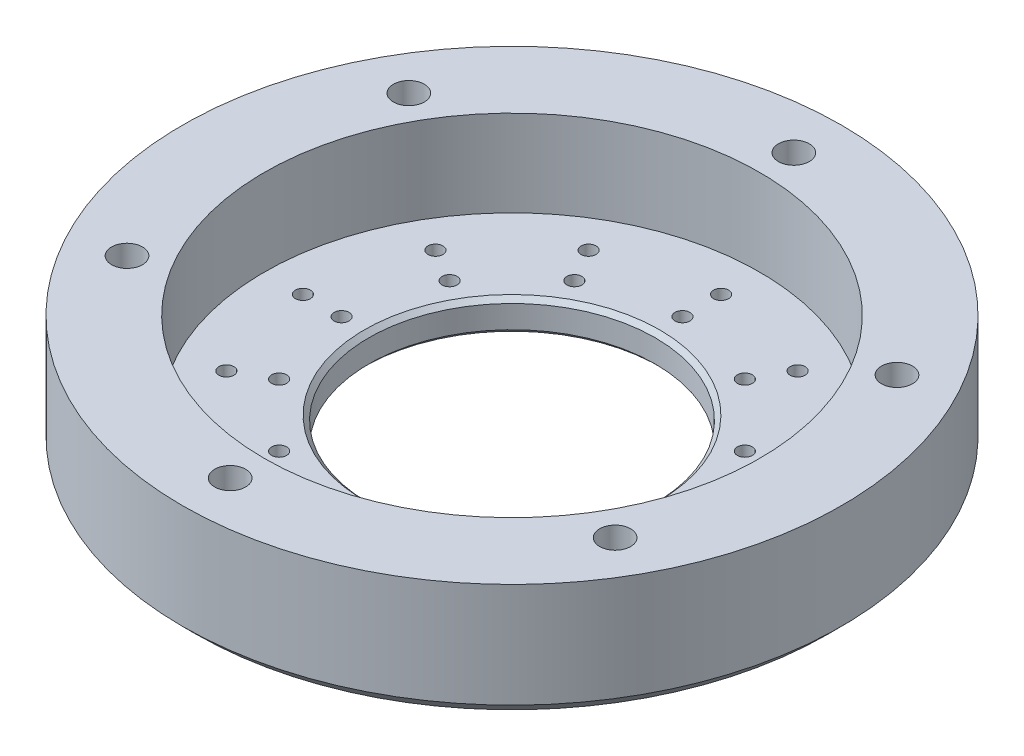
SolidWorks part; units mm, degrees
ref_plane "Piano frontale" through (0, 0, 0) normal (0, 0, 1) x (1, 0, 0)
ref_plane "Piano superiore" through (0, 0, 0) normal (0, 1, 0) x (1, 0, 0)
ref_plane "Piano destro" through (0, 0, 0) normal (1, 0, 0) x (0, 0, -1)
sketch "Schizzo1" plane through (0, 0, 0) normal (0, 0, 1) x (1, 0, 0)
  line L0 (0, 82.5741) -> (0, -57.0556) construction
  line L1 (72.5, 31.5594) -> (72.5, 5.5594)
  line L2 (72.5, 5.5594) -> (31.5, 5.5594)
  line L3 (31.5, 5.5594) -> (31.5, 12.5594)
  line L4 (31.5, 12.5594) -> (54.5, 12.5594)
  line L5 (54.5, 12.5594) -> (54.5, 31.5594)
  line L6 (54.5, 31.5594) -> (72.5, 31.5594)
  point P7 (58.1763, 32.9815)
  point P10 (72.5, 5.5594)
  dimension "D1" = 26
  dimension "D2" = 145
  dimension "D3" = 63
  dimension "D4" = 19
  dimension "D5" = 109
revolve "Rivoluzione1" add sketch "Schizzo1" angle 360 about L0
chamfer "Smusso1" distance 3 angle 45 1 edges at (0, 5.5594, 72.5)
chamfer "Smusso2" distance 1 angle 45 2 edges at (0, 5.5594, 31.5) (0, 12.5594, 31.5)
hole_wizard "Foro filettato M8-1" positions "Schizzo2" profile "Schizzo3" tap size "M8" standard "ISO"
sketch "Schizzo2" plane through (0, 31.5594, 0) normal (0, 1, 0) x (1, 0, 0)
  line L0 (0, 0) -> (0, 82.26) construction
  circle A0 centre (0, 0) radius 62 construction
  point P11 (0, 62)
  dimension "D1" = 124
sketch "Schizzo3" plane through (0, 31.5594, -62) normal (1, 0, 0) x (0, 0, 1)
  line L0 (0, 0) -> (0, 21.0429)
  line L1 (0, 21.0429) -> (3.4, 19)
  line L2 (3.4, 19) -> (3.4, 0)
  line L5 (3.4, 0) -> (0, 0)
  line L10 (0, 21.0429) -> (-3.4, 19) construction
  line L11 (0, -6.35) -> (0, 107.95) construction
  dimension "Tap Drill Dia." = 6.8
  dimension "Tap Drill Depth" = 19
  dimension "Drill Angle" = 118
cosmetic thread "Filettatura del foro1" parameters "D1"=16, "D2"=8
pattern_circular "RipetizioneCircolare1" count 6 over 360 about axis through (0, 0, 0) along (0, 1, 0) of "Foro filettato M8-1"
cosmetic thread "Filettatura del foro2" parameters "D1"=16, "D2"=8
cosmetic thread "Filettatura del foro3" parameters "D1"=16, "D2"=8
cosmetic thread "Filettatura del foro4" parameters "D1"=16, "D2"=8
cosmetic thread "Filettatura del foro5" parameters "D1"=16, "D2"=8
cosmetic thread "Filettatura del foro6" parameters "D1"=16, "D2"=8
hole_wizard "Foro filettato M4-1" positions "Schizzo4" profile "Schizzo5" tap size "M4" standard "ISO" end condition through all
sketch "Schizzo4" plane through (0, 12.5594, 0) normal (0, 1, 0) x (1, 0, 0)
  line L0 (0, 0) -> (0, 90.7044) construction
  circle A0 centre (0, 0) radius 46 construction
  circle A1 centre (0, 0) radius 37.5 construction
  point P13 (0, 37.5)
  point P15 (0, 46)
  dimension "D1" = 92
  dimension "D2" = 75
sketch "Schizzo5" plane through (0, 12.5594, -46) normal (1, 0, 0) x (0, 0, 1)
  line L0 (0, 0) -> (0, 7)
  line L1 (0, 7) -> (1.65, 7)
  line L2 (1.65, 7) -> (1.65, 0)
  line L5 (1.65, 0) -> (0, 0)
  line L11 (0, -6.35) -> (0, 107.95) construction
  dimension "Thru Tap Drill Dia." = 3.3
  dimension "Thru Tap Drill Depth" = 7
cosmetic thread "Filettatura del foro7" parameters "D2"=4
cosmetic thread "Filettatura del foro8" parameters "D2"=4
pattern_circular "RipetizioneCircolare2" count 12 over 360 about axis through (0, 0, 0) along (0, 1, 0) of "Foro filettato M4-1"
cosmetic thread "Filettatura del foro9" parameters "D2"=4
cosmetic thread "Filettatura del foro10" parameters "D2"=4
cosmetic thread "Filettatura del foro11" parameters "D2"=4
cosmetic thread "Filettatura del foro12" parameters "D2"=4
cosmetic thread "Filettatura del foro13" parameters "D2"=4
cosmetic thread "Filettatura del foro14" parameters "D2"=4
cosmetic thread "Filettatura del foro15" parameters "D2"=4
cosmetic thread "Filettatura del foro16" parameters "D2"=4
cosmetic thread "Filettatura del foro17" parameters "D2"=4
cosmetic thread "Filettatura del foro18" parameters "D2"=4
cosmetic thread "Filettatura del foro19" parameters "D2"=4
cosmetic thread "Filettatura del foro20" parameters "D2"=4
cosmetic thread "Filettatura del foro21" parameters "D2"=4
cosmetic thread "Filettatura del foro22" parameters "D2"=4
cosmetic thread "Filettatura del foro23" parameters "D2"=4
cosmetic thread "Filettatura del foro24" parameters "D2"=4
cosmetic thread "Filettatura del foro25" parameters "D2"=4
cosmetic thread "Filettatura del foro26" parameters "D2"=4
cosmetic thread "Filettatura del foro27" parameters "D2"=4
cosmetic thread "Filettatura del foro28" parameters "D2"=4
cosmetic thread "Filettatura del foro29" parameters "D2"=4
cosmetic thread "Filettatura del foro30" parameters "D2"=4
